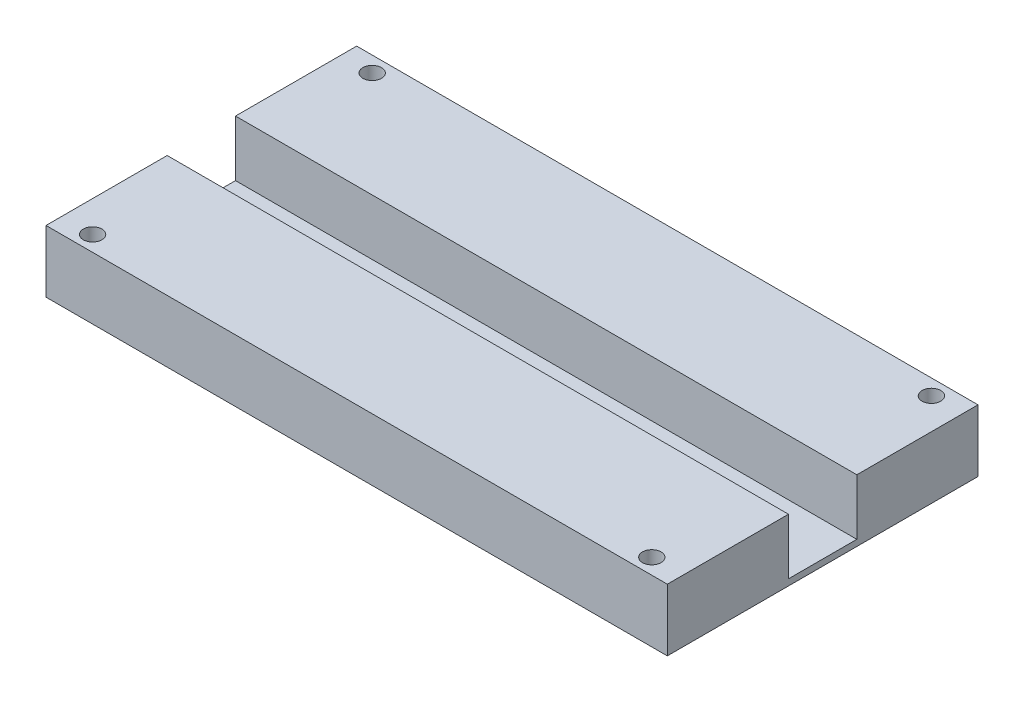
SolidWorks part; units mm, degrees
ref_plane "Front Plane" through (0, 0, 0) normal (0, 0, 1) x (1, 0, 0)
ref_plane "Top Plane" through (0, 0, 0) normal (0, 1, 0) x (1, 0, 0)
ref_plane "Right Plane" through (0, 0, 0) normal (1, 0, 0) x (0, 0, -1)
sketch "Sketch1" plane through (0, 0, 0) normal (0, 1, 0) x (1, 0, 0)
  line L1 (-30, -30) -> (70, -30)
  line L2 (-30, -30) -> (-30, 20)
  line L3 (-30, 20) -> (70, 20)
  line L4 (70, -30) -> (70, 20)
  circle A0 centre (-25, 17.5) radius 1.5
  circle A1 centre (-25, -27.5) radius 1.5
  circle A2 centre (65, 17.5) radius 1.5
  circle A3 centre (65, -27.5) radius 1.5
  point P0 (0, 0)
  dimension "D3" = 3
  dimension "D6" = 5
  dimension "D8" = 2.5
  dimension "D1" = 100
  dimension "D2" = 50
  dimension "D4" = 2.5
  dimension "D5" = 5
  dimension "D7" = 2.5
  dimension "D9" = 5
extrude "Boss-Extrude2" add sketch "Sketch1" along normal blind 10
sketch "Sketch2" plane through (0, 10, 0) normal (0, 1, 0) x (1, 0, 0)
  line L0 (70, -30) -> (70, 20) construction
  line L1 (70, 0.5) -> (-30, 0.5)
  line L2 (70, 0.5) -> (70, -10.5)
  line L3 (70, -10.5) -> (-30, -10.5)
  line L4 (-30, 0.5) -> (-30, -10.5)
  line L5 (-30, 20) -> (-30, -30) construction
  line L6 (70, 20) -> (-30, 20) construction
  dimension "D1" = 11
  dimension "D2" = 19.5
extrude "Cut-Extrude1" cut sketch "Sketch2" against normal blind 9
